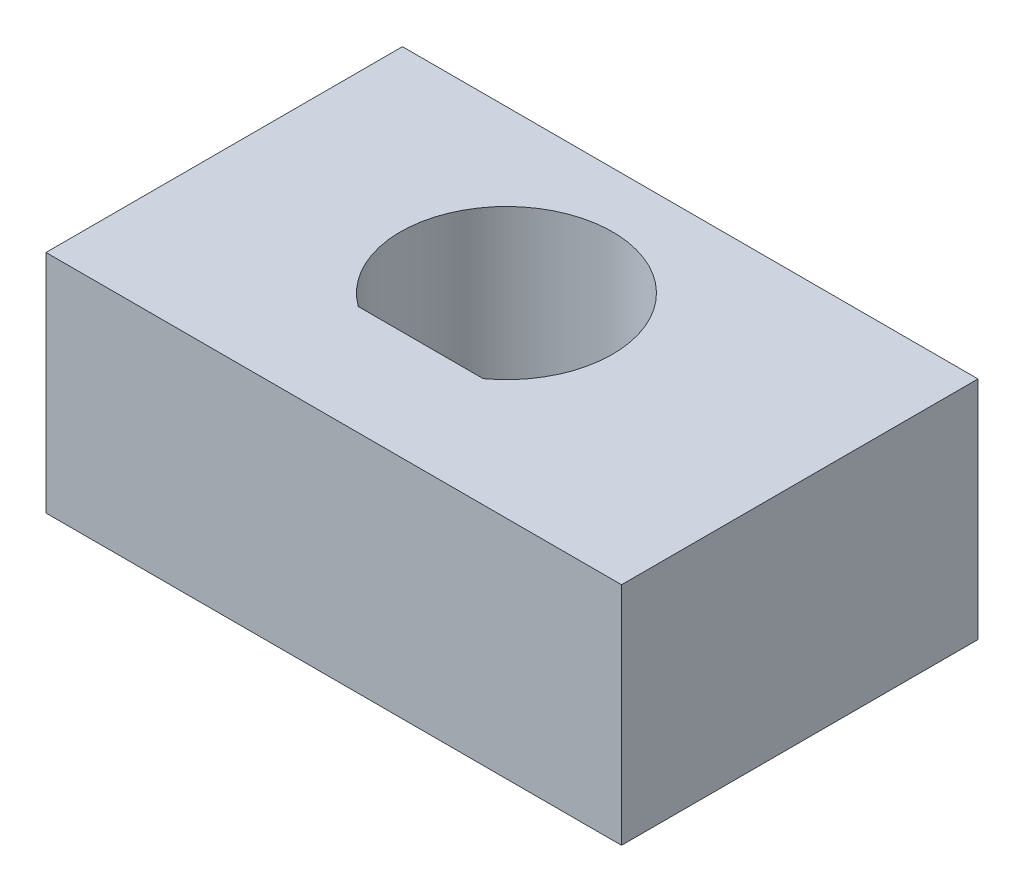
SolidWorks part; units mm, degrees
ref_plane "Front Plane" through (0, 0, 0) normal (0, 0, 1) x (1, 0, 0)
ref_plane "Top Plane" through (0, 0, 0) normal (0, 1, 0) x (1, 0, 0)
ref_plane "Right Plane" through (0, 0, 0) normal (1, 0, 0) x (0, 0, -1)
sketch "Sketch1" plane through (0, 0, 0) normal (0, 1, 0) x (1, 0, 0)
  line L0 (-2.7659, -3.8) -> (2.7659, -3.8)
  line L1 (-8.5985, 4.7) -> (8.5985, 4.7) construction
  line L3 (-11.759, 7.151) -> (13.7404, 7.151)
  line L4 (-11.759, 7.151) -> (-11.759, -8.6423)
  line L5 (-11.759, -8.6423) -> (13.7404, -8.6423)
  line L6 (13.7404, 7.151) -> (13.7404, -8.6423)
  circle A0 centre (0, 0) radius 4.7 construction
  arc A1 (-2.7659, -3.8) -> (2.7659, -3.8) centre (0, 0) cw
  point P2 (0, 4.7)
  dimension "D1" = 9.4
  dimension "D2" = 8.5
extrude "Boss-Extrude1" add sketch "Sketch1" along normal blind 10
